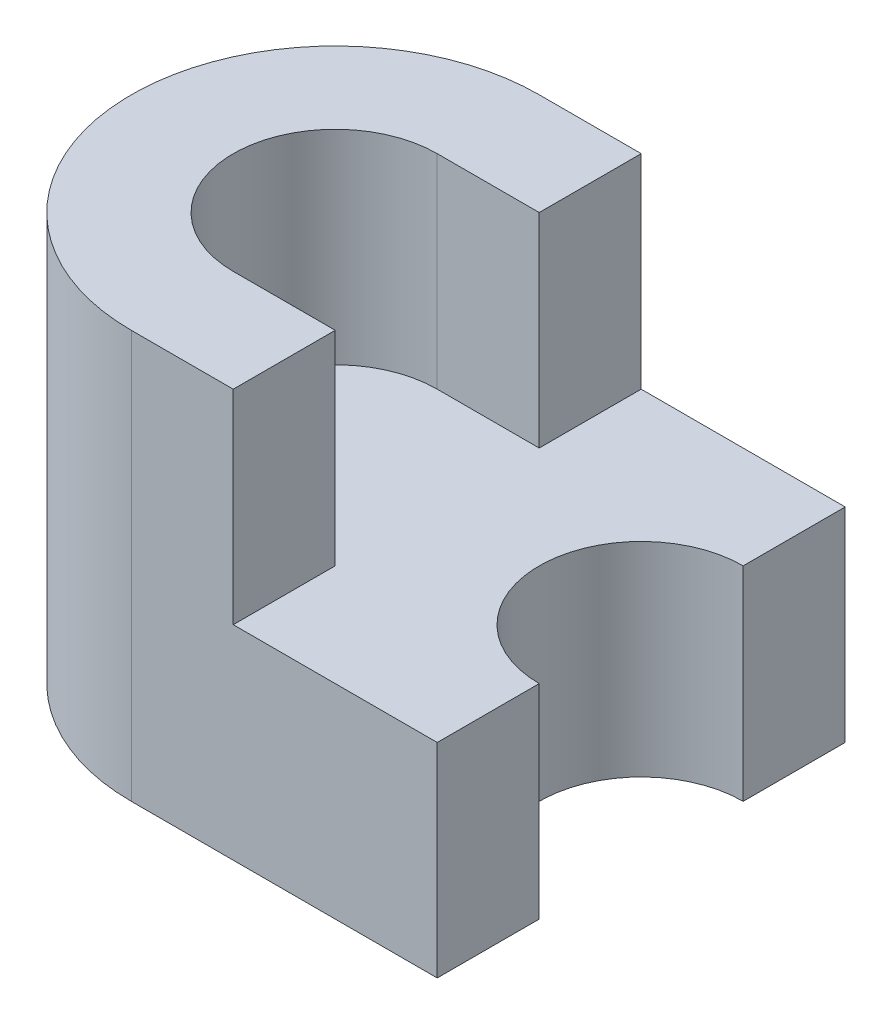
SolidWorks part; units mm, degrees
ref_plane "前基準面" through (0, 0, 0) normal (0, 0, 1) x (1, 0, 0)
ref_plane "上基準面" through (0, 0, 0) normal (0, 1, 0) x (1, 0, 0)
ref_plane "右基準面" through (0, 0, 0) normal (1, 0, 0) x (0, 0, -1)
sketch "草圖2" plane through (0, 0, 0) normal (0, 1, 0) x (1, 0, 0)
  line L0 (0, 5) -> (0, 10)
  line L1 (0, 10) -> (-15, 10)
  line L2 (-25, 0) -> (0, 0) construction
  line L3 (0, -5) -> (0, -10)
  line L4 (0, -10) -> (-15, -10)
  arc A0 (0, 5) -> (0, -5) centre (0, 0) ccw
  arc A1 (-15, 10) -> (-15, -10) centre (-15, 0) ccw
  point P1 (-12.1134, -22.3196)
  point P7 (0, 0)
  point P8 (0, 0)
  dimension "D1" = 10
  dimension "D2" = 5
  dimension "D3" = 15
extrude "填料-伸長1" add sketch "草圖2" along normal blind 10
sketch "草圖3" plane through (0, 10, 0) normal (0, 1, 0) x (1, 0, 0)
  line L0 (-10, 10) -> (-10, 5)
  line L1 (0, 10) -> (-15, 10) construction
  line L2 (-10, 5) -> (-15, 5)
  line L3 (-15, 5) -> (-15, -5) construction
  line L4 (-15, -5) -> (-10, -5)
  line L5 (-10, -5) -> (-10, -10)
  line L6 (-15, -10) -> (0, -10) construction
  line L7 (-10, -10) -> (-15, -10)
  line L8 (-15, 10) -> (-10, 10)
  line L9 (-10, 10) -> (-10.011, 10.0404)
  arc A0 (-15, 10) -> (-15, -10) centre (-15, 0) ccw construction
  arc A1 (-15, 10) -> (-15, -10) centre (-15, 0) ccw
  arc A2 (-15, 5) -> (-15, -5) centre (-15, 0) ccw
  line M3 (0, 10) -> (-15, 10)
  arc M4 (-15, 10) -> (-15, -10) centre (-15, 0) ccw
  line M5 (-15, -10) -> (0, -10)
  dimension "D1" = 10
  dimension "D2" = 5
  dimension "D3" = 5
extrude "填料-伸長2" add sketch "草圖3" along normal blind 10 contours A2 L2 L0 L5 L4 M3 M4 M5
